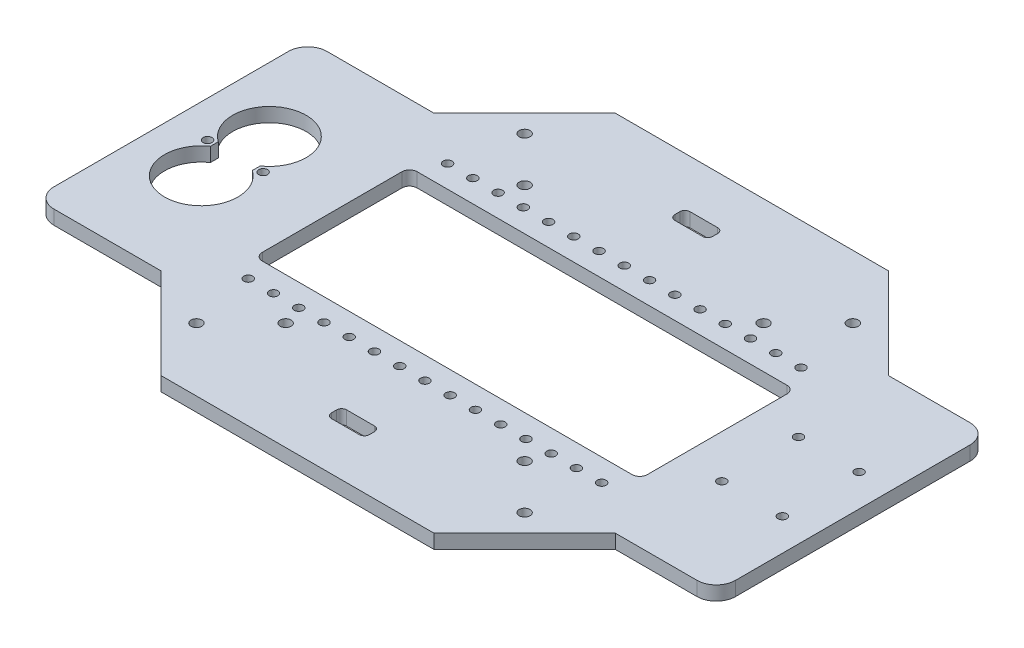
SolidWorks part; units mm, degrees
ref_plane "Front Plane" through (0, 0, 0) normal (0, 0, 1) x (1, 0, 0)
ref_plane "Top Plane" through (0, 0, 0) normal (0, 1, 0) x (1, 0, 0)
ref_plane "Right Plane" through (0, 0, 0) normal (1, 0, 0) x (0, 0, -1)
sketch "Sketch1" plane through (0, 0, 0) normal (0, 1, 0) x (1, 0, 0)
  line L0 (-73.2542, 28.5227) -> (-37.3332, 64.4437)
  line L1 (-37.3332, 64.4437) -> (70.8248, 64.4437)
  line L2 (70.8248, 64.4437) -> (106.7458, 28.5227)
  line L3 (106.7458, 28.5227) -> (106.7458, -79.6353)
  line L4 (106.7458, -79.6353) -> (70.8248, -115.5563)
  line L5 (70.8248, -115.5563) -> (-37.3332, -115.5563)
  line L6 (-37.3332, -115.5563) -> (-73.2542, -79.6353)
  line L7 (-73.2542, -79.6353) -> (-73.2542, 28.5227)
  dimension "D1" = 180
  dimension "D2" = 50.8
  dimension "D3" = 180
extrude "Boss-Extrude1" add sketch "Sketch1" along normal blind 5.588
sketch "Sketch2" plane through (0, 5.588, 0) normal (0, 1, 0) x (1, 0, 0)
  line L0 (-48.2542, 39.4437) -> (81.7458, 39.4437) construction
  line L1 (81.7458, 39.4437) -> (81.7458, -90.5563) construction
  line L2 (81.7458, -90.5563) -> (-48.2542, -90.5563) construction
  line L3 (-48.2542, -90.5563) -> (-48.2542, 39.4437) construction
  line L4 (-30.5765, 21.766) -> (64.0681, 21.766) construction
  line L5 (64.0681, 21.766) -> (64.0681, -72.8786) construction
  line L6 (64.0681, -72.8786) -> (-30.5765, -72.8786) construction
  line L7 (-30.5765, -72.8786) -> (-30.5765, 21.766) construction
  line L8 (-48.2542, 39.4437) -> (-30.5765, 21.766) construction
  line L9 (64.0681, 21.766) -> (81.7458, 39.4437) construction
  line L10 (-48.2542, -90.5563) -> (-30.5765, -72.8786) construction
  line L11 (64.0681, -72.8786) -> (81.7458, -90.5563) construction
  line L12 (-73.2542, -25.5563) -> (-48.2542, -25.5563) construction
  line L13 (-73.2542, 28.5227) -> (-73.2542, -79.6353) construction
  line L14 (16.7458, 39.4437) -> (16.7458, 64.4437) construction
  line L15 (70.8248, 64.4437) -> (-37.3332, 64.4437) construction
  line L19 (81.7458, -25.5563) -> (106.7458, -25.5563) construction
  line L20 (106.7458, -79.6353) -> (106.7458, 28.5227) construction
  line L21 (16.7458, -90.5563) -> (16.7458, -115.5563) construction
  line L22 (-37.3332, -115.5563) -> (70.8248, -115.5563) construction
  circle A0 centre (-48.2542, 39.4437) radius 2.159
  circle A1 centre (-30.5765, 21.766) radius 2.159
  circle A2 centre (-48.2542, -90.5563) radius 2.159
  circle A3 centre (-30.5765, -72.8786) radius 2.159
  circle A4 centre (64.0681, 21.766) radius 2.159
  circle A5 centre (81.7458, 39.4437) radius 2.159
  circle A6 centre (64.0681, -72.8786) radius 2.159
  circle A7 centre (81.7458, -90.5563) radius 2.159
  dimension "D1" = 4.318
  dimension "D2" = 25
  dimension "D3" = 130
  dimension "D4" = 94.6447
extrude "Cut-Extrude1" cut sketch "Sketch2" against normal through all
sketch "Sketch3" plane through (0, 5.588, 0) normal (0, 1, 0) x (1, 0, 0)
  line L5 (-59.5092, 5.1137) -> (93.0008, 5.1137)
  line L6 (-59.5092, 5.1137) -> (-59.5092, -56.2263)
  line L7 (-59.5092, -56.2263) -> (93.0008, -56.2263)
  line L12 (93.0008, 5.1137) -> (93.0008, -56.2263)
  line L16 (-73.2542, -25.5563) -> (106.7458, -25.5563) construction
  line L17 (-73.2542, 28.5227) -> (-73.2542, -79.6353) construction
  line L18 (106.7458, -79.6353) -> (106.7458, 28.5227) construction
  line L19 (16.7458, -115.5563) -> (16.7458, 64.4437) construction
  line L20 (-37.3332, -115.5563) -> (70.8248, -115.5563) construction
  line L21 (70.8248, 64.4437) -> (-37.3332, 64.4437) construction
  dimension "D2" = 152.51
  dimension "D4" = 61.34
extrude "Cut-Extrude2" cut sketch "Sketch3" against normal through all
sketch "Sketch5" plane through (0, 5.588, 0) normal (0, 1, 0) x (1, 0, 0)
  line L1 (-73.2542, -79.6353) -> (-115.6342, -79.6353)
  line L2 (-73.2542, -79.6353) -> (-73.2542, 28.5227)
  line L3 (-73.2542, 28.5227) -> (-115.6342, 28.5227)
  line L4 (-123.2542, -72.0153) -> (-123.2542, 20.9027)
  arc A0 (-115.6342, -79.6353) -> (-123.2542, -72.0153) centre (-115.6342, -72.0153) cw
  arc A1 (-123.2542, 20.9027) -> (-115.6342, 28.5227) centre (-115.6342, 20.9027) cw
  point P10 (-123.2542, 28.5227)
  dimension "D2" = 7.62
  dimension "D1" = 50
extrude "Boss-Extrude2" add sketch "Sketch5" against normal up to surface (5.588 mm away) up to face at (16.7458, 0, 25.5563)
sketch "Sketch6" plane through (0, 5.588, 0) normal (0, 1, 0) x (1, 0, 0)
  line L1 (106.7458, 28.5227) -> (139.1258, 28.5227)
  line L2 (106.7458, 28.5227) -> (106.7458, -79.6353)
  line L3 (106.7458, -79.6353) -> (139.1258, -79.6353)
  line L4 (146.7458, 20.9027) -> (146.7458, -72.0153)
  arc A0 (139.1258, 28.5227) -> (146.7458, 20.9027) centre (139.1258, 20.9027) cw
  arc A1 (146.7458, -72.0153) -> (139.1258, -79.6353) centre (139.1258, -72.0153) cw
  point P8 (146.7458, 28.5227)
  dimension "D2" = 7.62
  dimension "D1" = 40
extrude "Boss-Extrude3" add sketch "Sketch6" against normal up to surface (5.588 mm away) up to face at (16.7458, 0, 25.5563)
sketch "Sketch7" plane through (0, 5.588, 0) normal (0, 1, 0) x (1, 0, 0)
  line L0 (110.0458, -40.7563) -> (110.0458, -10.3563) construction
  line L1 (110.0458, -10.3563) -> (134.0458, -10.3563) construction
  line L2 (134.0458, -10.3563) -> (134.0458, -40.7563) construction
  line L3 (134.0458, -40.7563) -> (110.0458, -40.7563) construction
  line L4 (-123.2542, -25.5563) -> (146.7458, -25.5563) construction
  line L5 (-123.2542, 20.9027) -> (-123.2542, -72.0153) construction
  line L6 (146.7458, -72.0153) -> (146.7458, 20.9027) construction
  circle A0 centre (110.0458, -10.3563) radius 1.75
  circle A1 centre (134.0458, -10.3563) radius 1.75
  circle A2 centre (110.0458, -40.7563) radius 1.75
  circle A3 centre (134.0458, -40.7563) radius 1.75
  dimension "D3" = 3.5
  dimension "D1" = 24
  dimension "D2" = 30.4
  dimension "D4" = 12.7
extrude "Cut-Extrude4" cut sketch "Sketch7" against normal through all
sketch "Sketch8" plane through (0, 5.588, 0) normal (0, 1, 0) x (1, 0, 0)
  line L0 (-106.1542, -24.0067) -> (-106.1542, -27.1059)
  line L1 (-89.5542, -24.0067) -> (-89.5542, -27.1059)
  line L2 (-97.8542, -12.0563) -> (-97.8542, -39.0563) construction
  line L3 (-123.2542, -25.5563) -> (146.7458, -25.5563) construction
  line L4 (-123.2542, 20.9027) -> (-123.2542, -72.0153) construction
  line L5 (146.7458, -72.0153) -> (146.7458, 20.9027) construction
  arc A0 (-106.1542, -27.1059) -> (-89.5542, -27.1059) centre (-97.8542, -39.0563) ccw
  arc A1 (-89.5542, -24.0067) -> (-106.1542, -24.0067) centre (-97.8542, -12.0563) ccw
  circle A2 centre (-108.8542, -25.5563) radius 1.75
  circle A3 centre (-86.8542, -25.5563) radius 1.75
  dimension "D1" = 29.1
  dimension "D5" = 3.5
  dimension "D2" = 27
  dimension "D3" = 16.6
  dimension "D4" = 22
  dimension "D6" = 25.4
extrude "Cut-Extrude6" cut sketch "Sketch8" against normal through all
sketch "Sketch9" plane through (0, 5.588, 0) normal (0, 1, 0) x (1, 0, 0)
  line L2 (16.7458, 64.4437) -> (16.7458, -115.5563) construction
  line L3 (70.8248, 64.4437) -> (-37.3332, 64.4437) construction
  line L4 (-37.3332, -115.5563) -> (70.8248, -115.5563) construction
  line L5 (93.0008, 5.1137) -> (-59.5092, 5.1137) construction
  line L6 (-123.2542, -25.5563) -> (146.7458, -25.5563) construction
  line L7 (-123.2542, 20.9027) -> (-123.2542, -72.0153) construction
  line L8 (146.7458, -72.0153) -> (146.7458, 20.9027) construction
  circle A0 centre (-53.2542, 13.9237) radius 1.75
  circle A1 centre (-43.2542, 13.9237) radius 1.75
  circle A2 centre (-33.2542, 13.9237) radius 1.75
  circle A3 centre (-23.2542, 13.9237) radius 1.75
  circle A4 centre (-13.2542, 13.9237) radius 1.75
  circle A5 centre (-3.2542, 13.9237) radius 1.75
  circle A6 centre (6.7458, 13.9237) radius 1.75
  circle A7 centre (16.7458, 13.9237) radius 1.75
  circle A8 centre (26.7458, 13.9237) radius 1.75
  circle A9 centre (36.7458, 13.9237) radius 1.75
  circle A10 centre (46.7458, 13.9237) radius 1.75
  circle A11 centre (56.7458, 13.9237) radius 1.75
  circle A12 centre (66.7458, 13.9237) radius 1.75
  circle A13 centre (76.7458, 13.9237) radius 1.75
  circle A14 centre (86.7458, 13.9237) radius 1.75
  circle A15 centre (-53.2542, -65.0363) radius 1.75
  circle A16 centre (-43.2542, -65.0363) radius 1.75
  circle A17 centre (-33.2542, -65.0363) radius 1.75
  circle A18 centre (-23.2542, -65.0363) radius 1.75
  circle A19 centre (-13.2542, -65.0363) radius 1.75
  circle A20 centre (-3.2542, -65.0363) radius 1.75
  circle A21 centre (6.7458, -65.0363) radius 1.75
  circle A22 centre (16.7458, -65.0363) radius 1.75
  circle A23 centre (26.7458, -65.0363) radius 1.75
  circle A24 centre (36.7458, -65.0363) radius 1.75
  circle A25 centre (46.7458, -65.0363) radius 1.75
  circle A26 centre (56.7458, -65.0363) radius 1.75
  circle A27 centre (66.7458, -65.0363) radius 1.75
  circle A28 centre (76.7458, -65.0363) radius 1.75
  circle A29 centre (86.7458, -65.0363) radius 1.75
  dimension "D1" = 3.5
  dimension "D4" = 3.5
  dimension "D3" = 8.81
  dimension "D6" = 78.96
  dimension "D7" = 140
  dimension "D8" = 10
  dimension "D2" = 15
  dimension "D5" = 15
extrude "Cut-Extrude8" cut sketch "Sketch9" against normal through all
sketch "Sketch10" plane through (0, 5.588, 0) normal (0, 1, 0) x (1, 0, 0)
  line L0 (-123.2542, -25.5563) -> (146.7458, -25.5563) construction
  line L1 (11.2458, 45.4437) -> (22.2458, 45.4437)
  line L2 (9.2458, 43.4437) -> (9.2458, 41.4437)
  line L3 (11.2458, 39.4437) -> (22.2458, 39.4437)
  line L4 (24.2458, 43.4437) -> (24.2458, 41.4437)
  line L5 (11.2458, -90.5563) -> (22.2458, -90.5563)
  line L6 (9.2458, -92.5563) -> (9.2458, -94.5563)
  line L7 (11.2458, -96.5563) -> (22.2458, -96.5563)
  line L8 (24.2458, -92.5563) -> (24.2458, -94.5563)
  line L9 (-123.2542, 20.9027) -> (-123.2542, -72.0153) construction
  line L10 (146.7458, -72.0153) -> (146.7458, 20.9027) construction
  line L11 (16.7458, -115.5563) -> (16.7458, 64.4437) construction
  line L12 (-37.3332, -115.5563) -> (70.8248, -115.5563) construction
  line L13 (70.8248, 64.4437) -> (-37.3332, 64.4437) construction
  arc A0 (9.2458, -94.5563) -> (11.2458, -96.5563) centre (11.2458, -94.5563) ccw
  arc A1 (22.2458, -96.5563) -> (24.2458, -94.5563) centre (22.2458, -94.5563) ccw
  arc A2 (24.2458, -92.5563) -> (22.2458, -90.5563) centre (22.2458, -92.5563) ccw
  arc A3 (11.2458, -90.5563) -> (9.2458, -92.5563) centre (11.2458, -92.5563) ccw
  arc A4 (9.2458, 41.4437) -> (11.2458, 39.4437) centre (11.2458, 41.4437) ccw
  arc A5 (22.2458, 39.4437) -> (24.2458, 41.4437) centre (22.2458, 41.4437) ccw
  arc A6 (24.2458, 43.4437) -> (22.2458, 45.4437) centre (22.2458, 43.4437) ccw
  arc A7 (11.2458, 45.4437) -> (9.2458, 43.4437) centre (11.2458, 43.4437) ccw
  point P32 (24.2458, 39.4437)
  point P35 (24.2458, 45.4437)
  point P38 (9.2458, 45.4437)
  dimension "D4" = 2
  dimension "D1" = 15
  dimension "D2" = 6
  dimension "D3" = 65
extrude "Cut-Extrude9" cut sketch "Sketch10" against normal through all
fillet "Fillet1" radius 3 4 edges at (-59.5092, 2.794, 56.2263) (93.0008, 2.794, 56.2263) (93.0008, 2.794, -5.1137) (-59.5092, 2.794, -5.1137)
